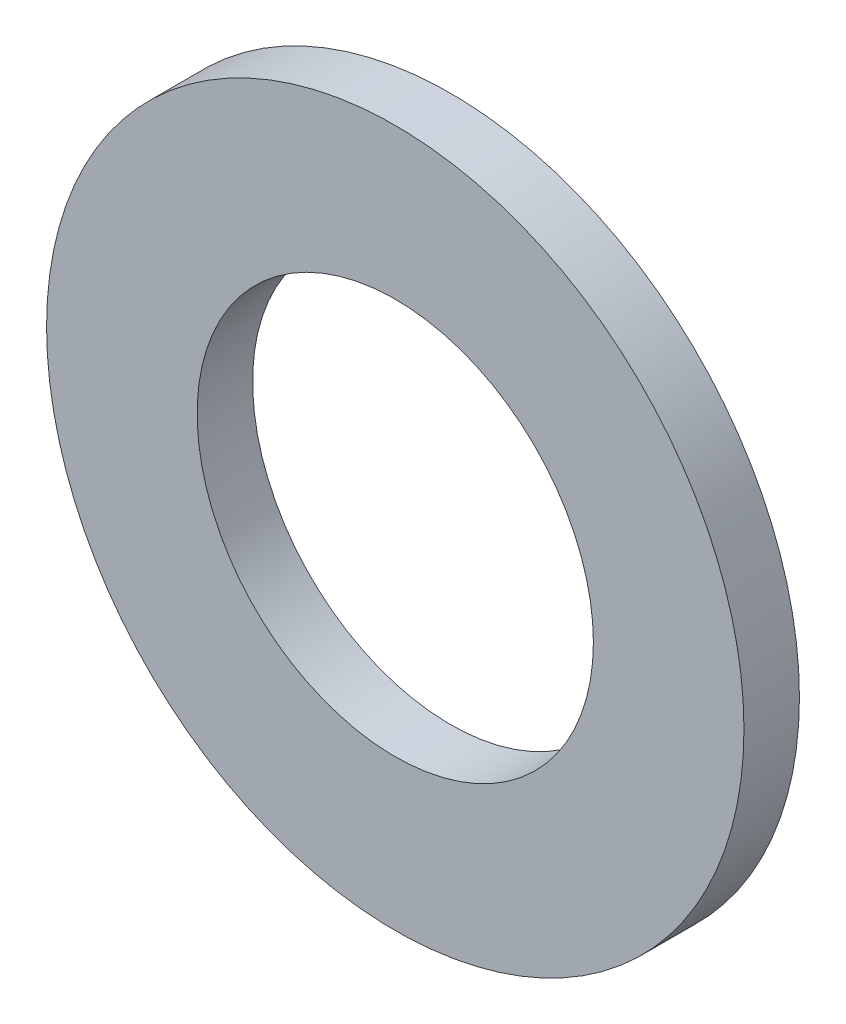
SolidWorks part; units mm, degrees
ref_plane "Front Plane" through (0, 0, 0) normal (0, 0, 1) x (1, 0, 0)
ref_plane "Top Plane" through (0, 0, 0) normal (0, 1, 0) x (1, 0, 0)
ref_plane "Right Plane" through (0, 0, 0) normal (1, 0, 0) x (0, 0, -1)
sketch "Sketch1" plane through (0, 0, 0) normal (0, 0, 1) x (1, 0, 0)
  circle A0 centre (0, 0) radius 12.5
  circle A1 centre (0, 0) radius 22
  dimension "D1" = 44
  dimension "D2" = 25
extrude "Boss-Extrude1" add sketch "Sketch1" along normal mid plane 3.5
